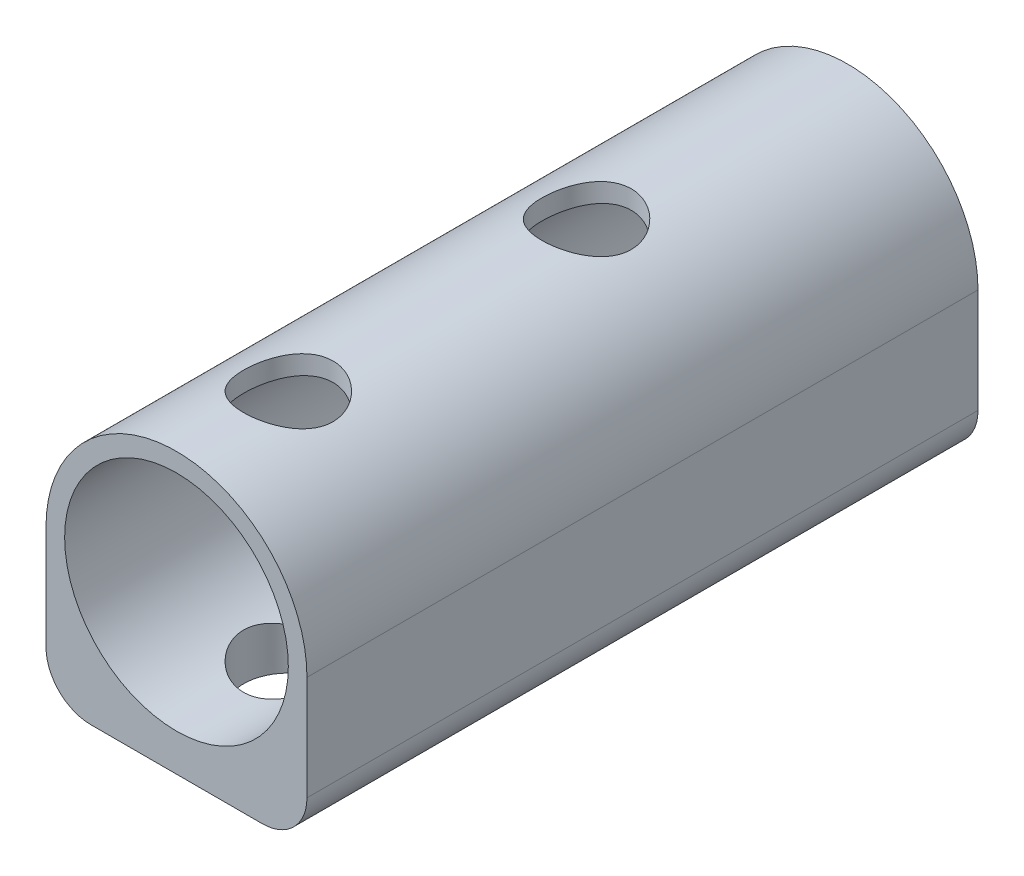
SolidWorks part; units mm, degrees
ref_plane "Plane1" through (0, 0, 0) normal (0, 0, 1) x (1, 0, 0)
ref_plane "Plane2" through (0, 0, 0) normal (0, 1, 0) x (1, 0, 0)
ref_plane "Plane3" through (0, 0, 0) normal (1, 0, 0) x (0, 0, -1)
sketch "Sketch1" plane through (0, 0, 0) normal (0, 0, 1) x (1, 0, 0)
  line L0 (-17.5, -20) -> (-17.5, 0)
  line L1 (17.5, 0) -> (17.5, -20)
  line L2 (17.5, -20) -> (-17.5, -20)
  arc A0 (-17.5, 0) -> (17.5, 0) centre (0, 0) cw
  dimension "D1" = 20
  dimension "D2" = 35
extrude "Base-Extrude" add sketch "Sketch1" along normal blind 90
sketch "Sketch2" plane through (0, 0, 90) normal (0, 0, 1) x (1, 0, 0)
  circle A0 centre (0, 0) radius 15
  dimension "D1" = 30
extrude "Cut-Extrude1" cut sketch "Sketch2" against normal through all
sketch "Sketch3" plane through (0, -20, 0) normal (0, -1, 0) x (1, 0, 0)
  line L0 (17.5, 90) -> (-17.5, 90) construction
  line L3 (17.5, 90) -> (-17.5, 90) construction
  circle A0 centre (0, 35) radius 6
  circle A1 centre (0, 75) radius 6
  dimension "D1" = 55
  dimension "D2" = 12
  dimension "D3" = 15
extrude "Cut-Extrude2" cut sketch "Sketch3" against normal through all
fillet "Fillet1" radius 6 2 edges at (17.5, -20, 45) (-17.5, -20, 45)
